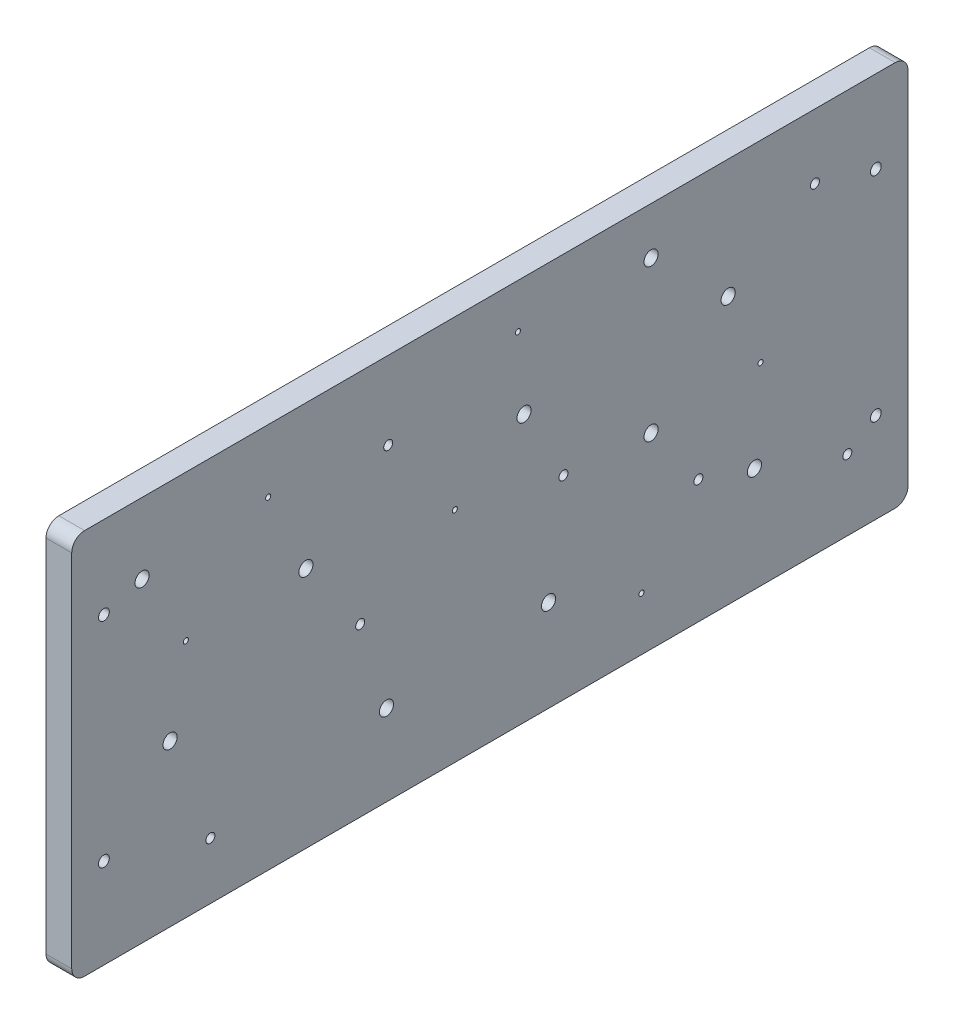
SolidWorks part; units mm, degrees
other "Markup1"
sketch "Sketch23" plane through (0, 0, -650) normal (-0.998, -0.0502, -0.0376) x (-0.0622, 0.868, 0.4926)
other "Markup2"
sketch "Sketch31" plane through (0, 0, -650) normal (-0.8797, -0.4745, -0.0329) x (0.01, -0.0876, 0.9961)
material "1060 Alloy"
ref_plane "Front Plane" through (0, 0, 0) normal (0, 0, 1) x (1, 0, 0)
ref_plane "Top Plane" through (0, 0, 0) normal (0, 1, 0) x (1, 0, 0)
ref_plane "Right Plane" through (0, 0, 0) normal (1, 0, 0) x (0, 0, -1)
sketch "Sketch1" plane through (0, 0, 0) normal (1, 0, 0) x (0, 0, -1)
  line L1 (0, 0) -> (650, 0)
  line L2 (0, 0) -> (0, 300)
  line L3 (0, 300) -> (650, 300)
  line L4 (650, 0) -> (650, 300)
  dimension "D1" = 650
  dimension "D2" = 300
extrude "Boss-Extrude1" add sketch "Sketch1" along normal blind 20
fillet "Fillet1" radius 10 4 edges at (10, 0, -650) (10, 300, -650) (10, 0, 0) (10, 300, 0)
sketch "Sketch4" plane through (20, 0, 0) normal (1, 0, 0) x (0, 0, -1)
  point P0 (54.6468, 244.9982)
  point P2 (530.6591, 81.5605)
  point P4 (510.2294, 207.5437)
  point P6 (244.6431, 63.1737)
  point P8 (181.992, 188.476)
  point P10 (351.5586, 207.5437)
  point P12 (370.6264, 71.3456)
  point P14 (76.4385, 125.1439)
  point P16 (450.3022, 145.5736)
  point P18 (450.3022, 263.3849)
hole_wizard "Ø11.0 (11) Diameter Hole1" positions "Sketch4" profile "Sketch3" hole size "Ø11.0" standard "DIN" end condition through all
sketch "Sketch3" plane through (20, 244.9982, -54.6468) normal (0, 1, 0) x (0, 0, -1)
  line L0 (0, 0) -> (0, 20)
  line L1 (0, 20) -> (5.5, 20)
  line L2 (5.5, 20) -> (5.5, 0)
  line L5 (5.5, 0) -> (0, 0)
  line L11 (0, -6.35) -> (0, 107.95) construction
  dimension "Thru Hole Dia." = 11
  dimension "Thru Hole Depth" = 20
sketch "Sketch7" plane through (20, 0, 0) normal (1, 0, 0) x (0, 0, -1)
  point P0 (107.7641, 44.106)
  point P2 (224.2134, 129.9108)
  point P4 (246.0051, 239.5502)
  point P6 (487.0757, 95.8613)
  point P8 (382.2032, 151.0215)
  point P10 (577.6474, 249.7651)
  point P12 (602.8441, 55.0018)
hole_wizard "Ø7.0 (7) Diameter Hole2" positions "Sketch7" profile "Sketch6" hole size "Ø7.0" standard "DIN" end condition through all
sketch "Sketch6" plane through (20, 44.106, -107.7641) normal (0, 1, 0) x (0, 0, -1)
  line L0 (0, 0) -> (0, 20)
  line L1 (0, 20) -> (3.5, 20)
  line L2 (3.5, 20) -> (3.5, 0)
  line L5 (3.5, 0) -> (0, 0)
  line L11 (0, -6.35) -> (0, 107.95) construction
  dimension "Thru Hole Dia." = 7
  dimension "Thru Hole Depth" = 20
sketch "Sketch10" plane through (20, 0, 0) normal (1, 0, 0) x (0, 0, -1)
  point P0 (152.7094, 251.1271)
  point P2 (88.6964, 186.433)
  point P4 (297.7604, 170.0892)
  point P6 (346.7917, 265.4279)
  point P10 (535.426, 150.3405)
  point P12 (442.8113, 41.382)
  point P14 (0, 0)
hole_wizard "Ø4.0 (4) Diameter Hole1" positions "Sketch10" profile "Sketch9" hole size "Ø4.0" standard "DIN" end condition through all
sketch "Sketch9" plane through (20, 251.1271, -152.7094) normal (0, 1, 0) x (0, 0, -1)
  line L0 (0, 0) -> (0, 20)
  line L1 (0, 20) -> (2, 20)
  line L2 (2, 20) -> (2, 0)
  line L5 (2, 0) -> (0, 0)
  line L11 (0, -6.35) -> (0, 107.95) construction
  dimension "Thru Hole Dia." = 4
  dimension "Thru Hole Depth" = 20
sketch "Sketch15" plane through (0, 0, 0) normal (0, -1, 0) x (-1, 0, 0)
  line L0 (-10, 640) -> (-10, 10) construction
  line L1 (0, 640) -> (-20, 640) construction
  line L2 (-20, 10) -> (0, 10) construction
  line L3 (-10, 10) -> (-10, 150) construction
  line L4 (-10, 640) -> (-10, 500) construction
  circle A0 centre (-10, 55) radius 2
  circle A1 centre (-10, 566.1661) radius 2
  dimension "D1" = 73.8339
  dimension "D2" = 45
  dimension "D3" = 140
  dimension "D4" = 140
sketch "Sketch20" plane through (0, 0, 0) normal (0, -1, 0) x (-1, 0, 0)
  line L0 (-10, 10) -> (-10, 150) construction
  line L1 (-20, 10) -> (0, 10) construction
  line L2 (-10, 640) -> (-10, 500) construction
  line L3 (0, 640) -> (-20, 640) construction
  point P1 (-10, 150)
  point P5 (-10, 500)
  point P15 (-10, 500)
  point P17 (-10, 150)
  dimension "D1" = 140
  dimension "D2" = 140
sketch "Sketch25" plane through (20, 0, 0) normal (1, 0, 0) x (0, 0, -1)
  line L0 (650, 10) -> (625, 10) construction
  line L1 (625, 10) -> (625, 70) construction
  line L2 (650, 290) -> (625, 290) construction
  line L3 (625, 290) -> (625, 235.86) construction
  line L4 (0, 290) -> (25, 290) construction
  line L5 (25, 290) -> (25, 235.86) construction
  line L6 (0, 10) -> (25, 10)
  line L7 (25, 10) -> (25, 70) construction
  point P4 (625, 70)
  point P8 (625, 235.86)
  point P12 (25, 235.86)
  point P16 (25, 70)
  point P29 (25, 70)
  point P31 (25, 235.86)
  point P33 (625, 235.86)
  point P35 (625, 70)
  dimension "D1" = 25
  dimension "D2" = 25
  dimension "D3" = 25
  dimension "D4" = 25
  dimension "D5" = 60
  dimension "D6" = 60
  dimension "D7" = 54.14
sketch "Sketch30" plane through (0, 0, 0) normal (-1, 0, 0) x (0, 0, 1)
  point P0 (-625, 235.86)
  point P3 (-625, 70)
  point P6 (-25, 70)
  point P9 (-25, 235.86)
  point P19 (0, 0)
  point P20 (0, 0)
  point P21 (0, 0)
  point P22 (0, 0)
hole_wizard "M8 Clearance Hole1" positions "Sketch30" profile "Sketch29" hole size "M8" standard "DIN" end condition through all
sketch "Sketch29" plane through (0, 235.86, -625) normal (0, 1, 0) x (0, 0, 1)
  line L0 (0, 0) -> (0, 20)
  line L1 (0, 20) -> (4.2, 20)
  line L2 (4.2, 20) -> (4.2, 0)
  line L5 (4.2, 0) -> (0, 0)
  line L11 (0, -6.35) -> (0, 107.95) construction
  dimension "Thru Hole Dia." = 8.4
  dimension "Thru Hole Depth" = 20
